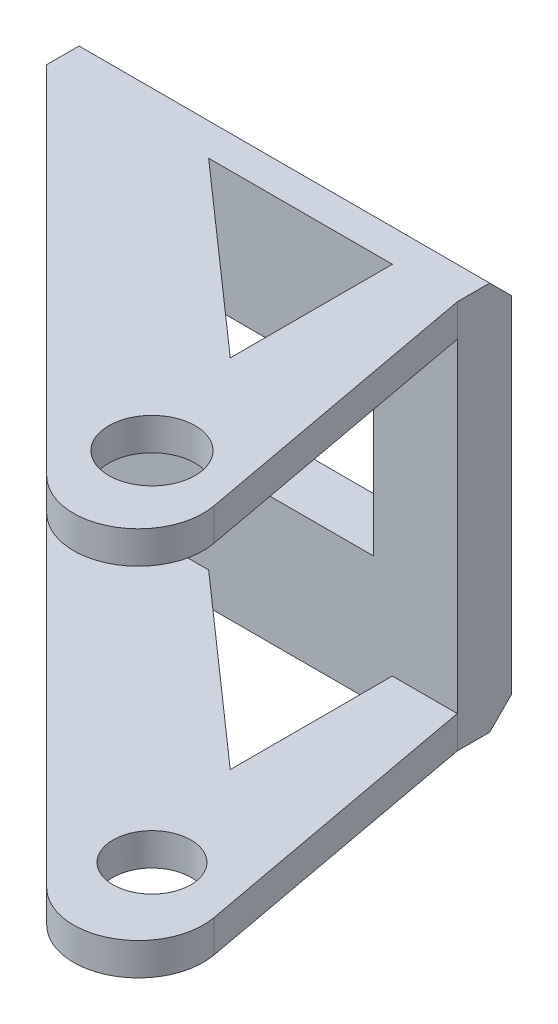
SolidWorks part; units mm, degrees
ref_plane "Alzado" through (0, 0, 0) normal (0, 0, 1) x (1, 0, 0)
ref_plane "Planta" through (0, 0, 0) normal (0, 1, 0) x (1, 0, 0)
ref_plane "Vista lateral" through (0, 0, 0) normal (1, 0, 0) x (0, 0, -1)
sketch "Croquis1" plane through (0, 0, 0) normal (0, 0, 1) x (1, 0, 0)
  line L1 (19, -18) -> (-19, -18)
  line L2 (19, -18) -> (19, 18)
  line L3 (19, 18) -> (-19, 18)
  line L4 (-19, -18) -> (-19, 18)
  line L5 (19, -18) -> (-19, 18) construction
  line L6 (19, 18) -> (-19, -18) construction
  line L7 (-11.25, -6.25) -> (11.25, -6.25)
  line L8 (-11.25, -6.25) -> (-11.25, 6.25)
  line L9 (-11.25, 6.25) -> (11.25, 6.25)
  line L10 (11.25, -6.25) -> (11.25, 6.25)
  line L11 (-11.25, -6.25) -> (11.25, 6.25) construction
  line L12 (-11.25, 6.25) -> (11.25, -6.25) construction
  point P0 (0, 0)
  point P6 (0, 0)
  dimension "D1" = 38
  dimension "D2" = 36
  dimension "D3" = 22.5
  dimension "D4" = 12.5
extrude "Saliente-Extruir1" add sketch "Croquis1" along normal blind 5
sketch "Croquis2" plane through (0, -18, 0) normal (0, -1, 0) x (1, 0, 0)
  line L0 (-19, 5) -> (27.6, 51.6)
  line L1 (-19, 5) -> (19, 5)
  line L2 (-19, 5) -> (27.6, 5) construction
  line L3 (27.6, 51.6) -> (19, 5)
  dimension "D1" = 46.6
extrude "Saliente-Extruir2" add sketch "Croquis2" against normal blind 3 separate body
fillet "Redondeo1" radius 6 1 edges at (27.6, -16.5, 51.6)
sketch "Croquis3" plane through (0, 18, 0) normal (0, 1, 0) x (1, 0, 0)
  line L0 (-19, -5) -> (19, -5)
  line L1 (19, -5) -> (24.0979, -32.6233)
  line L2 (-19, -5) -> (13.9549, -37.9549)
  arc A0 (24.0979, -32.6233) -> (13.9549, -37.9549) centre (18.1975, -33.7122) cw
extrude "Saliente-Extruir3" add sketch "Croquis3" against normal blind 3
sketch "Croquis4" plane through (0, 0, 0) normal (0, 0, -1) x (-1, 0, 0)
  line L1 (16.25, -6.25) -> (-16.25, -6.25)
  line L2 (16.25, -6.25) -> (16.25, 6.25)
  line L3 (16.25, 6.25) -> (-16.25, 6.25)
  line L4 (-16.25, -6.25) -> (-16.25, 6.25)
  line L5 (16.25, -6.25) -> (-16.25, 6.25) construction
  line L6 (16.25, 6.25) -> (-16.25, -6.25) construction
  point P0 (0, 0)
  dimension "D1" = 32.5
  dimension "D2" = 12.5
extrude "Cortar-Extruir1" cut sketch "Croquis4" against normal blind 1.5
sketch "Croquis5" plane through (0, -18, 0) normal (0, -1, 0) x (1, 0, 0)
  line L0 (-4.0119, 5) -> (12.9881, 5)
  line L1 (-19, 5) -> (19, 5) construction
  line L2 (12.9881, 5) -> (12.9881, 20)
  line L3 (12.9881, 20) -> (-4.0119, 5)
  dimension "D2" = 17
  dimension "D3" = 15
extrude "Cortar-Extruir2" cut sketch "Croquis5" against normal blind 41.5
chamfer "Chaflán1" distance 2 angle 45 2 edges at (0, 18, 0) (0, -18, 0)
sketch "Croquis6" plane through (0, -18, 0) normal (0, -1, 0) x (1, 0, 0)
  line L0 (20.9892, 39.0232) -> (18.1975, 33.7122) construction
  line L1 (18.1975, 33.7122) -> (16.8017, 31.0567) construction
  arc A0 (24.0979, 32.6233) -> (13.9549, 37.9549) centre (18.1975, 33.7122) ccw construction
  circle A1 centre (16.8017, 31.0567) radius 3.6
  dimension "D2" = 7.2
  dimension "D1" = 3
extrude "Cortar-Extruir4" cut sketch "Croquis6" against normal blind 10
sketch "Croquis7" plane through (0, 18, 0) normal (0, 1, 0) x (1, 0, 0)
  circle A0 centre (16.8017, -31.0567) radius 4
  dimension "D1" = 8
extrude "Cortar-Extruir5" cut sketch "Croquis7" against normal blind 10
